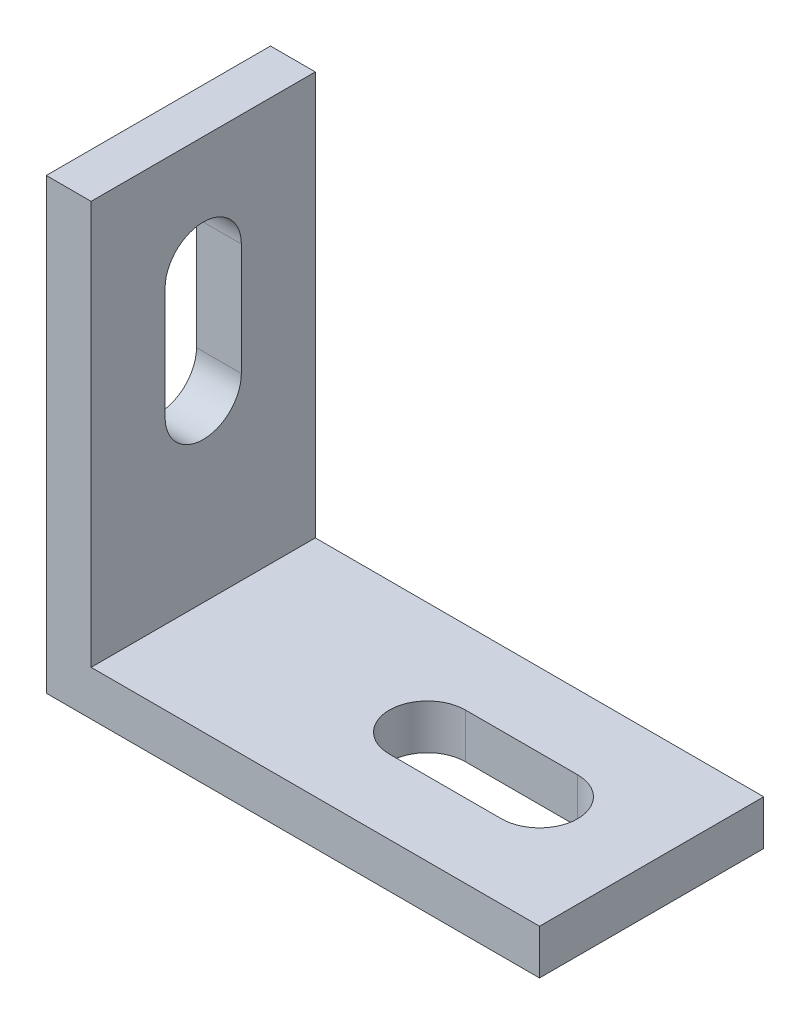
SolidWorks part; units mm, degrees
ref_plane "前视基准面" through (0, 0, 0) normal (0, 0, 1) x (1, 0, 0)
ref_plane "上视基准面" through (0, 0, 0) normal (0, 1, 0) x (1, 0, 0)
ref_plane "右视基准面" through (0, 0, 0) normal (1, 0, 0) x (0, 0, -1)
sketch "草图1" plane through (0, 0, 0) normal (0, 1, 0) x (1, 0, 0)
  line L0 (5, 0) -> (0, 0) construction
  line L1 (-10, -5) -> (10, -5)
  line L2 (-10, -5) -> (-10, 5)
  line L3 (-10, 5) -> (10, 5)
  line L4 (10, -5) -> (10, 5)
  line L5 (-10, -5) -> (10, 5) construction
  line L6 (-10, 5) -> (10, -5) construction
  line L7 (5, -1.7) -> (0, -1.7)
  line L8 (5, 1.7) -> (0, 1.7)
  arc A1 (5, -1.7) -> (5, 1.7) centre (5, 0) ccw
  arc A2 (0, 1.7) -> (0, -1.7) centre (0, 0) ccw
  point P0 (0, 0)
  point P8 (2.5, 0)
  dimension "D1" = 1.7
  dimension "D2" = 20
  dimension "D3" = 10
  dimension "D4" = 5
  dimension "D5" = 5
extrude "凸台-拉伸1" add sketch "草图1" along normal blind 2
sketch "草图3" plane through (-10, 0, 0) normal (-1, 0, 0) x (0, 0, 1)
  line L0 (0, 15) -> (0, 10) construction
  line L1 (-5, 0) -> (5, 0)
  line L2 (-5, 0) -> (-5, 20)
  line L3 (-5, 20) -> (5, 20)
  line L4 (5, 0) -> (5, 20)
  line L5 (1.7, 15) -> (1.7, 10)
  line L6 (-1.7, 15) -> (-1.7, 10)
  arc A0 (1.7, 15) -> (-1.7, 15) centre (0, 15) ccw
  arc A1 (-1.7, 10) -> (1.7, 10) centre (0, 10) ccw
  point P8 (0, 12.5)
  dimension "D4" = 1.7
  dimension "D1" = 20
  dimension "D2" = 5
  dimension "D3" = 5
extrude "凸台-拉伸3" add sketch "草图3" along normal blind 2
